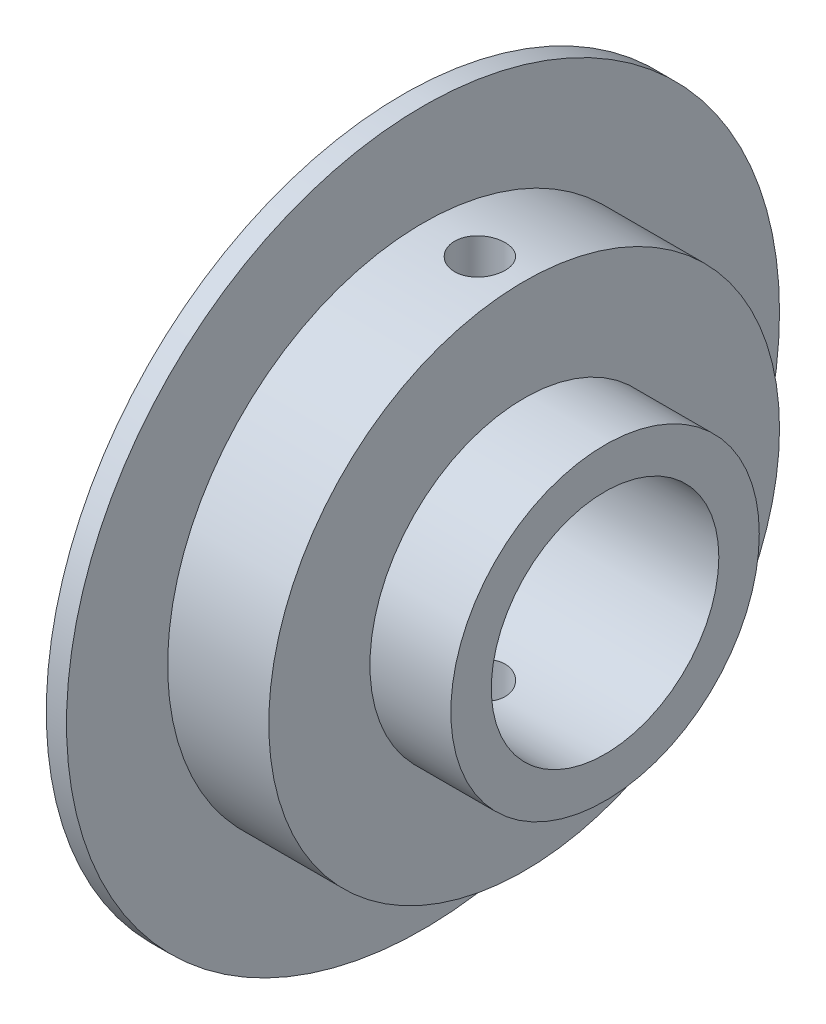
SolidWorks part; units mm, degrees
ref_plane "Front Plane" through (0, 0, 0) normal (0, 0, 1) x (1, 0, 0)
ref_plane "Top Plane" through (0, 0, 0) normal (0, 1, 0) x (1, 0, 0)
ref_plane "Right Plane" through (0, 0, 0) normal (1, 0, 0) x (0, 0, -1)
sketch "Sketch1" plane through (0, 0, 0) normal (0, 0, 1) x (1, 0, 0)
  line L0 (0, 0) -> (8, 0)
  line L1 (8, 0) -> (8, 1.6)
  line L2 (8, 1.6) -> (4.8, 1.6)
  line L3 (4.8, 1.6) -> (4.8, 5.6)
  line L4 (4.8, 5.6) -> (0.8, 5.6)
  line L5 (0.8, 5.6) -> (0.8, 9.6)
  line L6 (0.8, 9.6) -> (0, 9.6)
  line L7 (0, 9.6) -> (0, 0)
  point P6 (2.8, 5.6)
  dimension "D1" = 8
  dimension "D2" = 1.6
  dimension "D3" = 3.2
  dimension "D4" = 4
  dimension "D5" = 4
  dimension "D6" = 4
ref_plane "shaft_diamater_offset" through (0, -4.5, 0) normal (0, 1, 0) x (1, 0, 0)
ref_axis "Axis2" through (124.6316, -4.5, 0) along (-1, 0, 0)
revolve "Revolve1" add sketch "Sketch1" angle 360 about axis through (124.6316, -4.5, 0) along (-1, 0, 0)
sketch "Sketch4" plane through (0, -4.5, 0) normal (0, 1, 0) x (1, 0, 0)
  line L0 (4.8, -10.1) -> (4.8, 10.1) construction
  circle A0 centre (3.05, 0) radius 1
  dimension "D2" = 2
  dimension "D1" = 1.75
extrude "Cut-Extrude1" cut sketch "Sketch4" against normal through all both and the other way through all
equation "\"pulley_width\"=4"
equation "\"D5@Sketch1\"=\"pulley_width\""
equation "\"pu\"=3.5"
